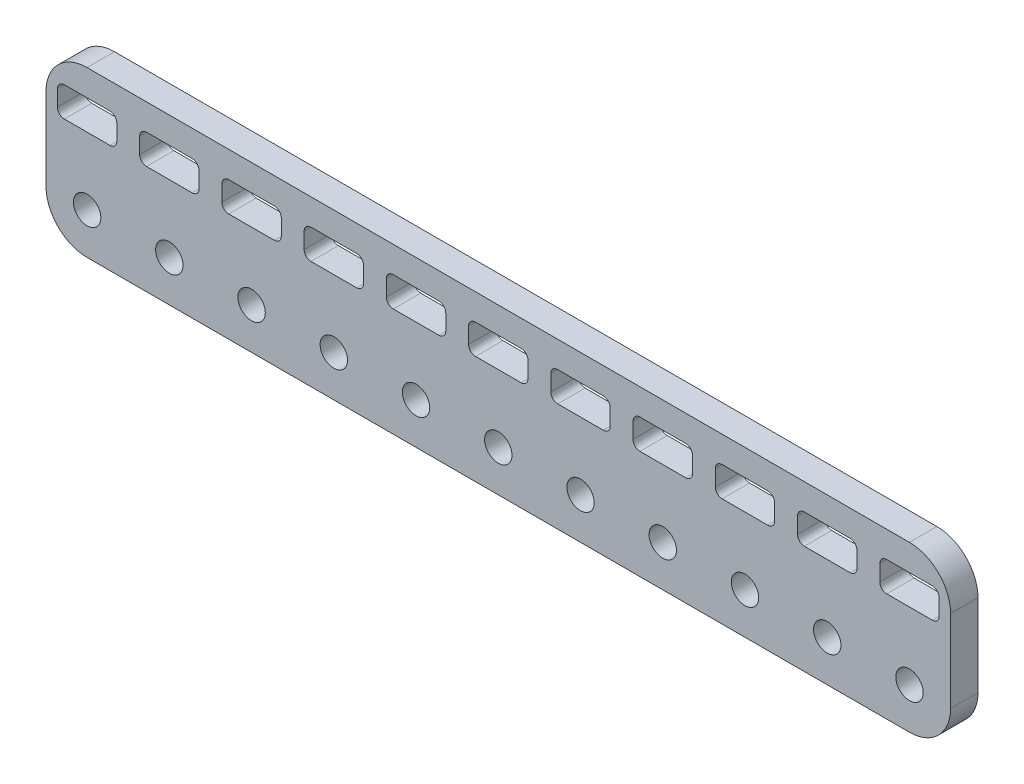
SolidWorks part; units mm, degrees
ref_plane "Alzado" through (0, 0, 0) normal (0, 0, 1) x (1, 0, 0)
ref_plane "Planta" through (0, 0, 0) normal (0, 1, 0) x (1, 0, 0)
ref_plane "Vista lateral" through (0, 0, 0) normal (1, 0, 0) x (0, 0, -1)
sketch "Model" plane through (0, 0, 0) normal (0, 0, 1) x (1, 0, 0)
  line L0 (256.4291, 228.7422) -> (346.4291, 228.7422)
  line L1 (346.4291, 210.7422) -> (256.4291, 210.7422)
  line L2 (350.9291, 224.2422) -> (350.9291, 215.2422)
  line L3 (251.9291, 224.2422) -> (251.9291, 215.2422)
  line L4 (267.9291, 222.6172) -> (262.9291, 222.6172)
  line L5 (262.1791, 223.3672) -> (262.1791, 225.1172)
  line L6 (262.9291, 225.8672) -> (267.9291, 225.8672)
  line L7 (268.6791, 225.1172) -> (268.6791, 223.3672)
  line L8 (285.9291, 222.6172) -> (280.9291, 222.6172)
  line L9 (280.1791, 223.3672) -> (280.1791, 225.1172)
  line L10 (280.9291, 225.8672) -> (285.9291, 225.8672)
  line L11 (286.6791, 225.1172) -> (286.6791, 223.3672)
  line L12 (276.9291, 222.6172) -> (271.9291, 222.6172)
  line L13 (271.1791, 223.3672) -> (271.1791, 225.1172)
  line L14 (271.9291, 225.8672) -> (276.9291, 225.8672)
  line L15 (277.6791, 225.1172) -> (277.6791, 223.3672)
  line L16 (294.9291, 222.6172) -> (289.9291, 222.6172)
  line L17 (289.1791, 223.3672) -> (289.1791, 225.1172)
  line L18 (289.9291, 225.8672) -> (294.9291, 225.8672)
  line L19 (295.6791, 225.1172) -> (295.6791, 223.3672)
  line L20 (303.9291, 222.6172) -> (298.9291, 222.6172)
  line L21 (298.1791, 223.3672) -> (298.1791, 225.1172)
  line L22 (298.9291, 225.8672) -> (303.9291, 225.8672)
  line L23 (304.6791, 225.1172) -> (304.6791, 223.3672)
  line L24 (321.9291, 222.6172) -> (316.9291, 222.6172)
  line L25 (316.1791, 223.3672) -> (316.1791, 225.1172)
  line L26 (316.9291, 225.8672) -> (321.9291, 225.8672)
  line L27 (322.6791, 225.1172) -> (322.6791, 223.3672)
  line L28 (312.9291, 222.6172) -> (307.9291, 222.6172)
  line L29 (307.1791, 223.3672) -> (307.1791, 225.1172)
  line L30 (307.9291, 225.8672) -> (312.9291, 225.8672)
  line L31 (313.6791, 225.1172) -> (313.6791, 223.3672)
  line L32 (258.9291, 222.6172) -> (253.9291, 222.6172)
  line L33 (253.1791, 223.3672) -> (253.1791, 225.1172)
  line L34 (253.9291, 225.8672) -> (258.9291, 225.8672)
  line L35 (259.6791, 225.1172) -> (259.6791, 223.3672)
  line L36 (348.9291, 222.6172) -> (343.9291, 222.6172)
  line L37 (343.1791, 223.3672) -> (343.1791, 225.1172)
  line L38 (343.9291, 225.8672) -> (348.9291, 225.8672)
  line L39 (349.6791, 225.1172) -> (349.6791, 223.3672)
  line L40 (339.9291, 222.6172) -> (334.9291, 222.6172)
  line L41 (334.1791, 223.3672) -> (334.1791, 225.1172)
  line L42 (334.9291, 225.8672) -> (339.9291, 225.8672)
  line L43 (340.6791, 225.1172) -> (340.6791, 223.3672)
  line L44 (330.9291, 222.6172) -> (325.9291, 222.6172)
  line L45 (325.1791, 223.3672) -> (325.1791, 225.1172)
  line L46 (325.9291, 225.8672) -> (330.9291, 225.8672)
  line L47 (331.6791, 225.1172) -> (331.6791, 223.3672)
  arc A0 (350.9291, 224.2422) -> (346.4291, 228.7422) centre (346.4291, 224.2422) ccw
  arc A1 (256.4291, 228.7422) -> (251.9291, 224.2422) centre (256.4291, 224.2422) ccw
  arc A2 (251.9291, 215.2422) -> (256.4291, 210.7422) centre (256.4291, 215.2422) ccw
  arc A3 (346.4291, 210.7422) -> (350.9291, 215.2422) centre (346.4291, 215.2422) ccw
  circle A4 centre (337.4291, 215.2422) radius 1.5
  circle A5 centre (319.4291, 215.2422) radius 1.5
  circle A6 centre (328.4291, 215.2422) radius 1.5
  circle A7 centre (310.4291, 215.2422) radius 1.5
  circle A8 centre (292.4291, 215.2422) radius 1.5
  circle A9 centre (301.4291, 215.2422) radius 1.5
  circle A10 centre (274.4291, 215.2422) radius 1.5
  circle A11 centre (283.4291, 215.2422) radius 1.5
  circle A12 centre (265.4291, 215.2422) radius 1.5
  circle A13 centre (256.4291, 215.2422) radius 1.5
  circle A14 centre (346.4291, 215.2422) radius 1.5
  arc A15 (262.1791, 223.3672) -> (262.9291, 222.6172) centre (262.9291, 223.3672) ccw
  arc A16 (262.9291, 225.8672) -> (262.1791, 225.1172) centre (262.9291, 225.1172) ccw
  arc A17 (268.6791, 225.1172) -> (267.9291, 225.8672) centre (267.9291, 225.1172) ccw
  arc A18 (267.9291, 222.6172) -> (268.6791, 223.3672) centre (267.9291, 223.3672) ccw
  arc A19 (280.1791, 223.3672) -> (280.9291, 222.6172) centre (280.9291, 223.3672) ccw
  arc A20 (280.9291, 225.8672) -> (280.1791, 225.1172) centre (280.9291, 225.1172) ccw
  arc A21 (286.6791, 225.1172) -> (285.9291, 225.8672) centre (285.9291, 225.1172) ccw
  arc A22 (285.9291, 222.6172) -> (286.6791, 223.3672) centre (285.9291, 223.3672) ccw
  arc A23 (271.1791, 223.3672) -> (271.9291, 222.6172) centre (271.9291, 223.3672) ccw
  arc A24 (271.9291, 225.8672) -> (271.1791, 225.1172) centre (271.9291, 225.1172) ccw
  arc A25 (277.6791, 225.1172) -> (276.9291, 225.8672) centre (276.9291, 225.1172) ccw
  arc A26 (276.9291, 222.6172) -> (277.6791, 223.3672) centre (276.9291, 223.3672) ccw
  arc A27 (289.1791, 223.3672) -> (289.9291, 222.6172) centre (289.9291, 223.3672) ccw
  arc A28 (289.9291, 225.8672) -> (289.1791, 225.1172) centre (289.9291, 225.1172) ccw
  arc A29 (295.6791, 225.1172) -> (294.9291, 225.8672) centre (294.9291, 225.1172) ccw
  arc A30 (294.9291, 222.6172) -> (295.6791, 223.3672) centre (294.9291, 223.3672) ccw
  arc A31 (298.1791, 223.3672) -> (298.9291, 222.6172) centre (298.9291, 223.3672) ccw
  arc A32 (298.9291, 225.8672) -> (298.1791, 225.1172) centre (298.9291, 225.1172) ccw
  arc A33 (304.6791, 225.1172) -> (303.9291, 225.8672) centre (303.9291, 225.1172) ccw
  arc A34 (303.9291, 222.6172) -> (304.6791, 223.3672) centre (303.9291, 223.3672) ccw
  arc A35 (316.1791, 223.3672) -> (316.9291, 222.6172) centre (316.9291, 223.3672) ccw
  arc A36 (316.9291, 225.8672) -> (316.1791, 225.1172) centre (316.9291, 225.1172) ccw
  arc A37 (322.6791, 225.1172) -> (321.9291, 225.8672) centre (321.9291, 225.1172) ccw
  arc A38 (321.9291, 222.6172) -> (322.6791, 223.3672) centre (321.9291, 223.3672) ccw
  arc A39 (307.1791, 223.3672) -> (307.9291, 222.6172) centre (307.9291, 223.3672) ccw
  arc A40 (307.9291, 225.8672) -> (307.1791, 225.1172) centre (307.9291, 225.1172) ccw
  arc A41 (313.6791, 225.1172) -> (312.9291, 225.8672) centre (312.9291, 225.1172) ccw
  arc A42 (312.9291, 222.6172) -> (313.6791, 223.3672) centre (312.9291, 223.3672) ccw
  arc A43 (253.1791, 223.3672) -> (253.9291, 222.6172) centre (253.9291, 223.3672) ccw
  arc A44 (253.9291, 225.8672) -> (253.1791, 225.1172) centre (253.9291, 225.1172) ccw
  arc A45 (259.6791, 225.1172) -> (258.9291, 225.8672) centre (258.9291, 225.1172) ccw
  arc A46 (258.9291, 222.6172) -> (259.6791, 223.3672) centre (258.9291, 223.3672) ccw
  arc A47 (343.1791, 223.3672) -> (343.9291, 222.6172) centre (343.9291, 223.3672) ccw
  arc A48 (343.9291, 225.8672) -> (343.1791, 225.1172) centre (343.9291, 225.1172) ccw
  arc A49 (349.6791, 225.1172) -> (348.9291, 225.8672) centre (348.9291, 225.1172) ccw
  arc A50 (348.9291, 222.6172) -> (349.6791, 223.3672) centre (348.9291, 223.3672) ccw
  arc A51 (334.1791, 223.3672) -> (334.9291, 222.6172) centre (334.9291, 223.3672) ccw
  arc A52 (334.9291, 225.8672) -> (334.1791, 225.1172) centre (334.9291, 225.1172) ccw
  arc A53 (340.6791, 225.1172) -> (339.9291, 225.8672) centre (339.9291, 225.1172) ccw
  arc A54 (339.9291, 222.6172) -> (340.6791, 223.3672) centre (339.9291, 223.3672) ccw
  arc A55 (325.1791, 223.3672) -> (325.9291, 222.6172) centre (325.9291, 223.3672) ccw
  arc A56 (325.9291, 225.8672) -> (325.1791, 225.1172) centre (325.9291, 225.1172) ccw
  arc A57 (331.6791, 225.1172) -> (330.9291, 225.8672) centre (330.9291, 225.1172) ccw
  arc A58 (330.9291, 222.6172) -> (331.6791, 223.3672) centre (330.9291, 223.3672) ccw
extrude "Saliente-Extruir1" add sketch "Model" along normal blind 3
